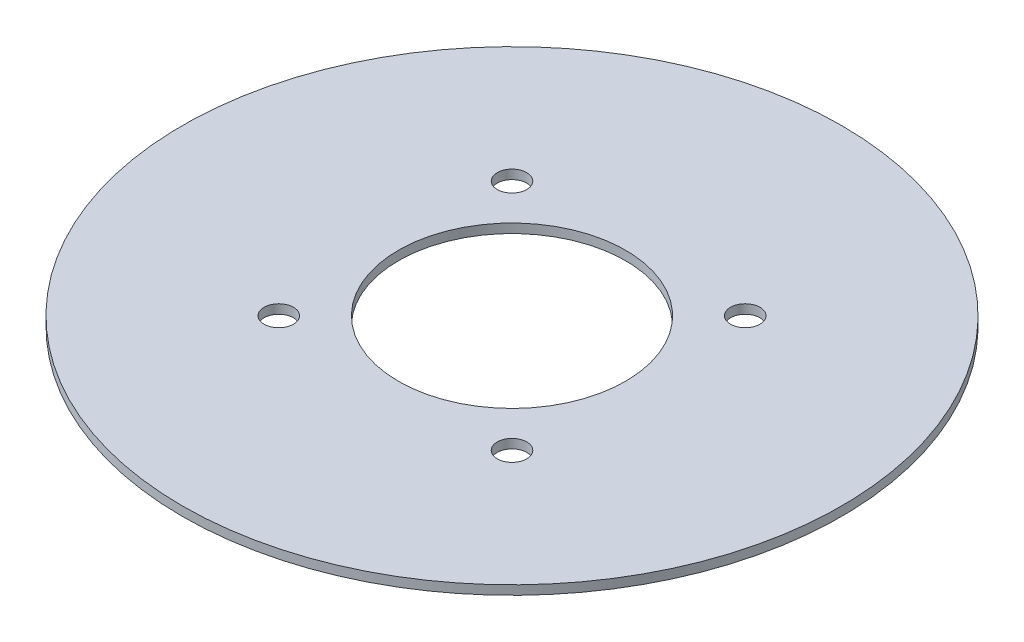
SolidWorks part; units mm, degrees
ref_plane "前视基准面" through (0, 0, 0) normal (0, 0, 1) x (1, 0, 0)
ref_plane "上视基准面" through (0, 0, 0) normal (0, 1, 0) x (1, 0, 0)
ref_plane "右视基准面" through (0, 0, 0) normal (1, 0, 0) x (0, 0, -1)
other "Configuration Table"
sketch "草图1" plane through (0, 606.0036, 0) normal (0, 1, 0) x (1, 0, 0)
  circle A0 centre (0, 0) radius 32.5
extrude "凸台-拉伸1" add sketch "草图1" along normal blind 0.9
sketch "草图2" plane through (0, 606.9036, 0) normal (0, 1, 0) x (1, 0, 0)
  circle A0 centre (11.5, 11.5) radius 1.45 construction
  circle A1 centre (11.5, -11.5) radius 1.45 construction
  circle A2 centre (-11.5, -11.5) radius 1.45 construction
  circle A3 centre (-11.5, 11.5) radius 1.45 construction
  circle A4 centre (0, 0) radius 11.2 construction
  circle A5 centre (11.5, 11.5) radius 1.45
  circle A6 centre (11.5, -11.5) radius 1.45
  circle A7 centre (-11.5, -11.5) radius 1.45
  circle A8 centre (-11.5, 11.5) radius 1.45
  circle A9 centre (0, 0) radius 11.2
extrude "切除-拉伸1" cut sketch "草图2" against normal blind 0.9
